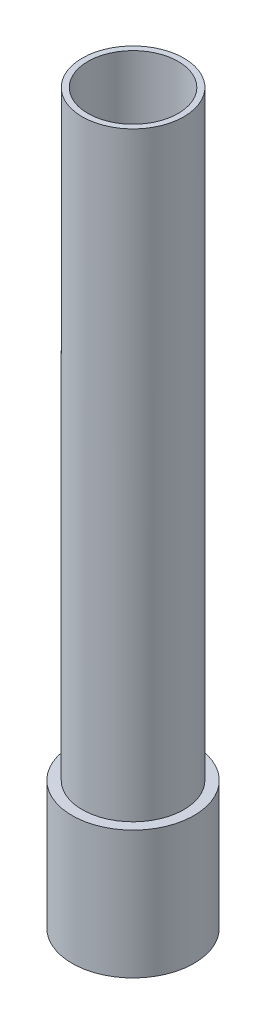
SolidWorks part; units mm, degrees
material "AISI 1020"
ref_plane "Front Plane" through (0, 0, 0) normal (0, 0, 1) x (1, 0, 0)
ref_plane "Top Plane" through (0, 0, 0) normal (0, 1, 0) x (1, 0, 0)
ref_plane "Right Plane" through (0, 0, 0) normal (1, 0, 0) x (0, 0, -1)
sketch "Sketch1" plane through (0, 0, 0) normal (0, 1, 0) x (1, 0, 0)
  circle A0 centre (13.6327, 6.0794) radius 7.0485
  circle A1 centre (13.6327, 6.0794) radius 7.9375
  dimension "D1" = 14.097
  dimension "D2" = 15.875
extrude "Boss-Extrude1" add sketch "Sketch1" along normal blind 113.72
sketch "Sketch2" plane through (0, 0, 0) normal (0, -1, 0) x (1, 0, 0)
  circle A0 centre (13.6327, -6.0794) radius 7.9375
  circle A1 centre (13.6327, -6.0794) radius 9.525
  dimension "D1" = 19.05
extrude "Boss-Extrude2" add sketch "Sketch2" against normal blind 20
